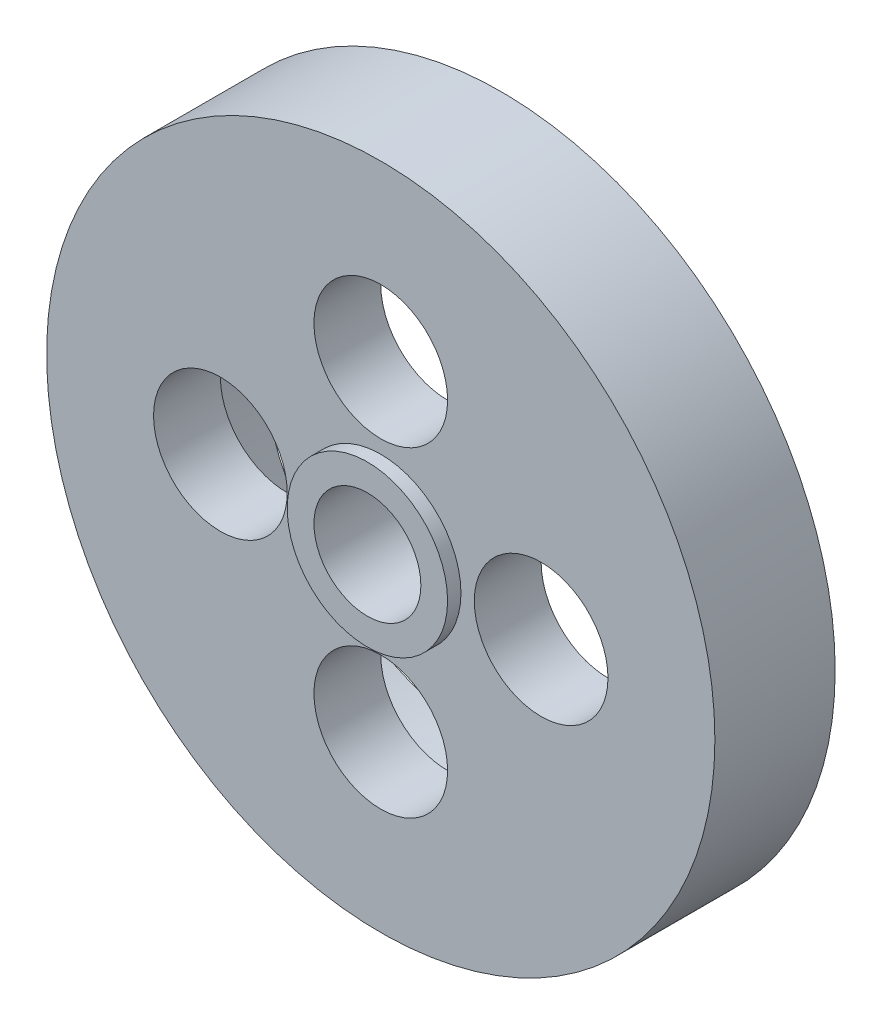
SolidWorks part; units mm, degrees
ref_plane "Front Plane" through (0, 0, 0) normal (0, 0, 1) x (1, 0, 0)
ref_plane "Top Plane" through (0, 0, 0) normal (0, 1, 0) x (1, 0, 0)
ref_plane "Right Plane" through (0, 0, 0) normal (1, 0, 0) x (0, 0, -1)
sketch "Sketch1" plane through (0, 0, 0) normal (0, 0, 1) x (1, 0, 0)
  circle A0 centre (0, 0) radius 12 construction
  circle A1 centre (0, 0) radius 25
  circle A2 centre (0, 12) radius 5
  circle A3 centre (12, 0) radius 5
  circle A4 centre (0, -12) radius 5
  circle A5 centre (-12, 0) radius 5
  circle A6 centre (0, 0) radius 4
  point P15 (0, 0)
  dimension "D1" = 24
  dimension "D2" = 50
  dimension "D3" = 10
  dimension "D4" = 8
extrude "Boss-Extrude1" add sketch "Sketch1" along normal blind 9
sketch "Sketch2" plane through (0, 0, 0) normal (0, 0, -1) x (-1, 0, 0)
  circle A0 centre (0, 0) radius 18
  dimension "D1" = 36
extrude "Cut-Extrude1" cut sketch "Sketch2" against normal blind 4
sketch "Sketch3" plane through (0, 0, 9) normal (0, 0, 1) x (1, 0, 0)
  circle A0 centre (0, 0) radius 6
  circle A1 centre (0, 0) radius 4 construction
  circle A2 centre (0, 0) radius 4
  dimension "D1" = 12
extrude "Boss-Extrude2" add sketch "Sketch3" along normal blind 1
